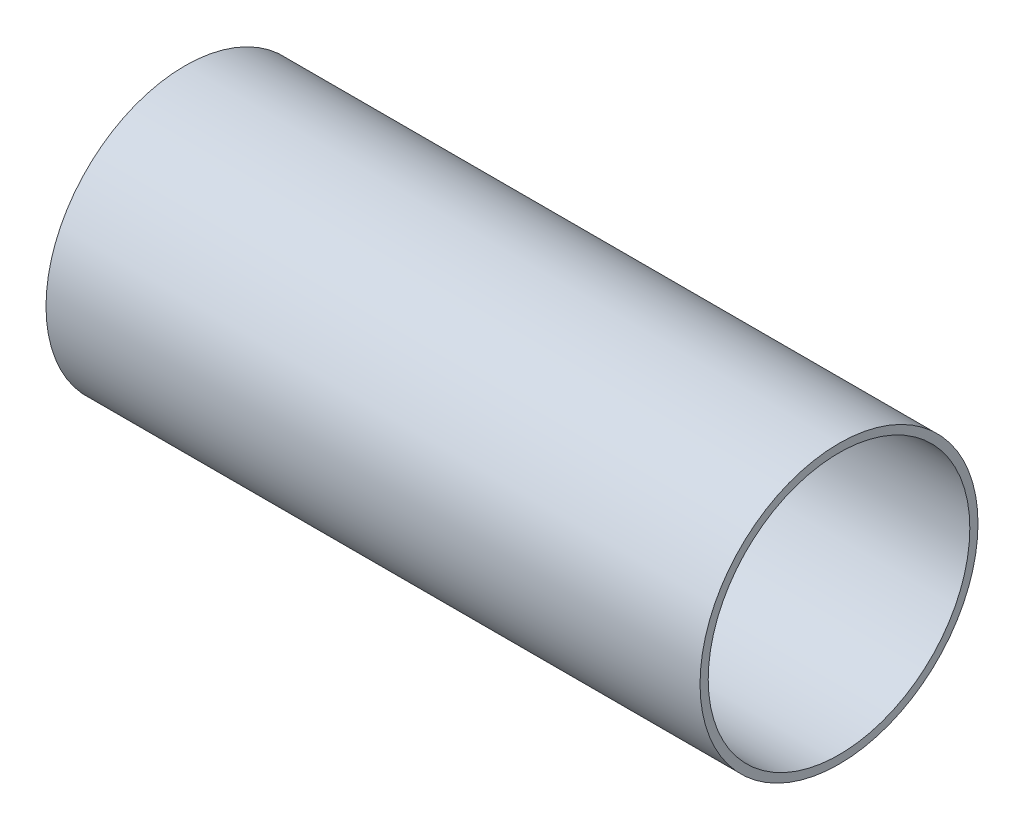
SolidWorks part; units mm, degrees
material "Corrugated Paper"
ref_plane "Front Plane" through (0, 0, 0) normal (0, 0, 1) x (1, 0, 0)
ref_plane "Top Plane" through (0, 0, 0) normal (0, 1, 0) x (1, 0, 0)
ref_plane "Right Plane" through (0, 0, 0) normal (1, 0, 0) x (0, 0, -1)
sketch "Sketch1" plane through (0, 0, 0) normal (0, 1, 0) x (1, 0, 0)
  line L0 (0, 4) -> (-20, 4)
  line L1 (-20, 4) -> (-20, 4.25)
  line L2 (-20, 4.25) -> (0, 4.25)
  line L3 (0, 4.25) -> (0, 4)
  dimension "D1" = 4
  dimension "D2" = 4.25
  dimension "D3" = 20
sketch "Sketch2" plane through (0, 0, 0) normal (0, 0, 1) x (1, 0, 0)
  line L0 (0, 0) -> (-41.9172, 0) construction
  dimension "D1" = 41.9172
revolve "Revolve2" add sketch "Sketch1" angle 360 about L0
